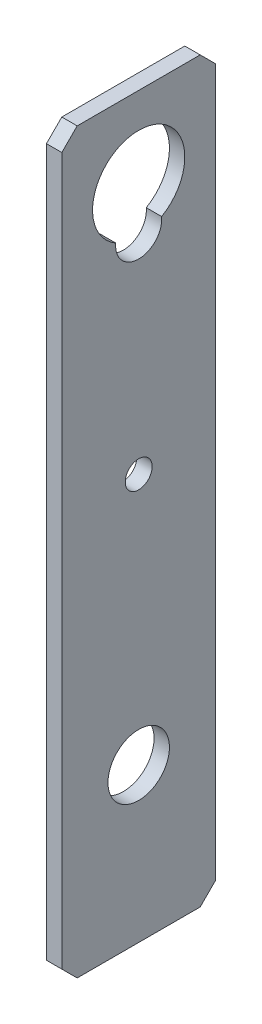
SolidWorks part; units mm, degrees
ref_plane "Front Plane" through (0, 0, 0) normal (0, 0, 1) x (1, 0, 0)
ref_plane "Top Plane" through (0, 0, 0) normal (0, 1, 0) x (1, 0, 0)
ref_plane "Right Plane" through (0, 0, 0) normal (1, 0, 0) x (0, 0, -1)
sketch "Sketch1" plane through (0, 0, 0) normal (1, 0, 0) x (0, 0, -1)
  line L1 (0, 0) -> (20, 0)
  line L2 (0, 0) -> (0, 96)
  line L3 (0, 96) -> (20, 96)
  line L4 (20, 0) -> (20, 96)
  dimension "D1" = 96
  dimension "D2" = 20
extrude "Boss-Extrude1" add sketch "Sketch1" along normal blind 2
sketch "Sketch2" plane through (2, 0, 0) normal (1, 0, 0) x (0, 0, -1)
  line L0 (10, 96) -> (10, 0) construction
  line L1 (20, 96) -> (0, 96) construction
  line L2 (0, 0) -> (20, 0) construction
  arc A0 (12.9854, 80.2955) -> (7.0146, 80.2955) centre (10, 85.5) ccw
  circle A1 centre (10, 52.75) radius 1.75
  circle A2 centre (10, 20) radius 4
  arc A4 (7.0146, 80.2955) -> (12.9854, 80.2955) centre (10, 80) ccw
  dimension "D1" = 8
  dimension "D2" = 3.5
  dimension "D3" = 12
  dimension "D5" = 32.75
  dimension "D6" = 10.5
  dimension "D7" = 6
  dimension "D8" = 0.5
  dimension "D4" = 20
extrude "Cut-Extrude1" cut sketch "Sketch2" against normal blind 2
chamfer "Chamfer1" distance 2 angle 45 4 edges at (1, 0, -20) (1, 0, 0) (1, 96, -20) (1, 96, 0)
